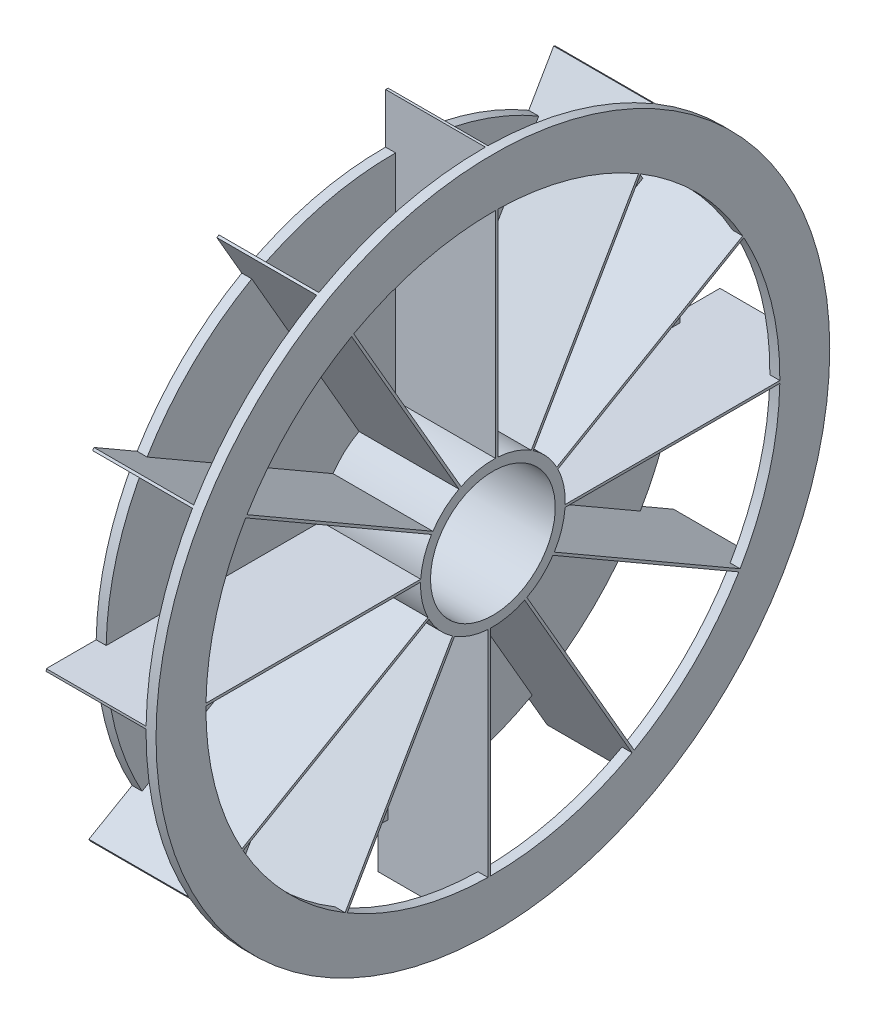
SolidWorks part; units mm, degrees
ref_plane "Plano frontal" through (0, 0, 0) normal (0, 0, 1) x (1, 0, 0)
ref_plane "Plano superior" through (0, 0, 0) normal (0, 1, 0) x (1, 0, 0)
ref_plane "Plano direito" through (0, 0, 0) normal (1, 0, 0) x (0, 0, -1)
sketch "Esboço1" plane through (0, 0, 0) normal (0, 0, 1) x (1, 0, 0)
  line L0 (0, 0) -> (44.1668, 0) construction
  line L1 (0, 12.5) -> (22, 12.5)
  line L2 (22, 12.5) -> (22, 67.5)
  line L3 (22, 67.5) -> (0, 67.5)
  line L4 (0, 67.5) -> (0, 12.5)
  dimension "D1" = 22
  dimension "D2" = 135
  dimension "D3" = 25
revolve "Revolução1" add sketch "Esboço1" angle 360 about L0
sketch "Esboço2" plane through (22, 0, 0) normal (1, 0, 0) x (0, 0, -1)
  line L0 (0, 14.5) -> (0, 57.5) construction
  line L1 (1, 14.4655) -> (1, 67.4926)
  line L2 (-1, 14.4655) -> (-1, 57.5)
  line L3 (1, 14.5) -> (1, 57.5) construction
  line L4 (-1, 14.5) -> (-1, 57.5) construction
  line L5 (9.3088, 11.1174) -> (30.8904, 48.4978)
  line L6 (7.6812, 12.2983) -> (34.1846, 58.2036)
  line L7 (8.753, 12.1547) -> (30.253, 49.3937) construction
  line L8 (0, -3.0059) -> (1, 14.4655) construction
  line L9 (0, -3.0059) -> (9.6017, 11.6248) construction
  circle A0 centre (0, 0) radius 67.5 construction
  circle A1 centre (0, 0) radius 67.5
  circle A2 centre (0, 0) radius 14.5
  circle A3 centre (0, 0) radius 14.5
  circle A5 centre (0, 0) radius 57.5
  circle A6 centre (0, 0) radius 57.5
  dimension "D5" = 30
  dimension "D1" = 2
  dimension "D2" = 10
  dimension "D3" = 1
  dimension "D4" = 1
extrude "Corte-extrusão1" cut sketch "Esboço2" against normal offset from surface (20 mm away) 2 contours L6 A6 L1 A3 up to face at (0, 0, 12.5)
ref_axis "Eixo1" through (0, 0, 0) along (1, 0, 0)
pattern_circular "CirPattern1" count 12 over 360 about axis through (0, 0, 0) along (1, 0, 0) of "Corte-extrusão1"
ref_plane "Plano1" through (20, 0, 0) normal (1, 0, 0) x (0, 0, -1)
sketch "Esboço3" plane through (20, 0, 0) normal (1, 0, 0) x (0, 0, -1)
  line L0 (7.6812, 12.2983) -> (34.1846, 58.2036) construction
  line L1 (1, 14.4655) -> (1, 67.4926) construction
  line L2 (29.1845, 49.5431) -> (34.1846, 58.2036)
  line L3 (1, 57.4913) -> (1, 67.4926)
  circle A0 centre (0, 0) radius 57.5 construction
  circle A1 centre (0, 0) radius 67.5 construction
  arc A2 (29.1845, 49.5431) -> (1, 57.4913) centre (0, 0) ccw
  arc A3 (34.1846, 58.2036) -> (1, 67.4926) centre (0, 0) ccw
extrude "Corte-extrusão2" cut sketch "Esboço3" against normal through all
pattern_circular "CirPattern2" count 12 over 360 about axis through (0, 0, 0) along (1, 0, 0) of "Corte-extrusão2"
